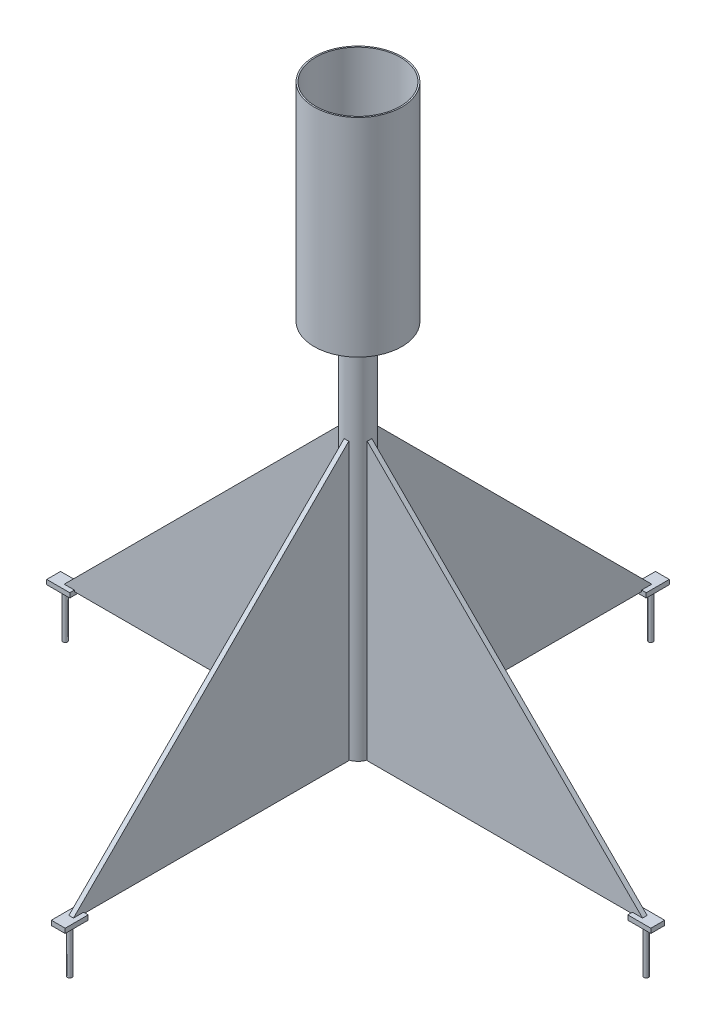
SolidWorks part; units mm, degrees
material "AISI 316 Stainless Steel Sheet (SS)"
ref_plane "Front Plane" through (0, 0, 0) normal (0, 0, 1) x (1, 0, 0)
ref_plane "Top Plane" through (0, 0, 0) normal (0, 1, 0) x (1, 0, 0)
ref_plane "Right Plane" through (0, 0, 0) normal (1, 0, 0) x (0, 0, -1)
sketch "Sketch1" plane through (0, 0, 0) normal (0, 1, 0) x (1, 0, 0)
  circle A0 centre (0, 0) radius 95
  dimension "D1" = 190
extrude "Boss-Extrude1" add sketch "Sketch1" along normal blind 450
shell "Shell2" thickness 3
sketch "Sketch2" plane through (0, 0, 0) normal (0, -1, 0) x (1, 0, 0)
  circle A0 centre (0, 0) radius 30
  dimension "D1" = 60
extrude "Boss-Extrude2" add sketch "Sketch2" along normal blind 805
shell "Shell3" thickness 3
sketch "Sketch5" plane through (0, 0, 0) normal (1, 0, 0) x (0, 0, -1)
  line L0 (-30, -805) -> (-30, -205) construction
  line L1 (-30, 0) -> (-30, -805) construction
  line L2 (-30, -205) -> (-630, -805) construction
  line L3 (-630, -805) -> (-30, -805) construction
  line L4 (-30, -205) -> (-630, -805)
  line L5 (-630, -805) -> (-30, -805)
  line L6 (-30, -805) -> (-30, -205)
  dimension "D1" = 600
  dimension "D2" = 600
extrude "Boss-Extrude3" add sketch "Sketch5" along normal blind 10 separate body
sketch "Sketch6" plane through (0, 0, 0) normal (1, 0, 0) x (0, 0, -1)
  line L0 (30, -805) -> (30, -205) construction
  line L1 (30, -805) -> (30, 0) construction
  line L2 (30, -205) -> (630, -805) construction
  line L3 (630, -805) -> (30, -805) construction
  line L4 (30, -205) -> (30, -805)
  line L5 (30, -805) -> (630, -805)
  line L6 (630, -805) -> (30, -205)
  dimension "D1" = 600
  dimension "D2" = 600
extrude "Boss-Extrude4" add sketch "Sketch6" along normal blind 10 separate body
sketch "Sketch8" plane through (0, 0, 0) normal (0, 0, 1) x (1, 0, 0)
  line L0 (-30, -805) -> (-30, -205) construction
  line L1 (-30, 0) -> (-30, -805) construction
  line L2 (-30, -205) -> (-630, -805) construction
  line L3 (-630, -805) -> (-30, -805) construction
  line L4 (-30, -205) -> (-30, -805)
  line L5 (-30, -805) -> (-630, -805)
  line L6 (-630, -805) -> (-30, -205)
  dimension "D1" = 600
  dimension "D2" = 600
extrude "Boss-Extrude5" add sketch "Sketch8" along normal blind 10 separate body
sketch "Sketch9" plane through (0, 0, 0) normal (0, 0, 1) x (1, 0, 0)
  line L0 (30, -805) -> (30, -205) construction
  line L1 (30, -805) -> (30, 0) construction
  line L2 (30, -205) -> (630, -805) construction
  line L3 (630, -805) -> (30, -805) construction
  line L4 (30, -205) -> (30, -805)
  line L5 (30, -805) -> (630, -805)
  line L6 (630, -805) -> (30, -205)
  dimension "D1" = 600
  dimension "D2" = 600
extrude "Boss-Extrude6" add sketch "Sketch9" along normal blind 10 separate body
ref_plane "Plane4" through (0, -802, 0) normal (0, -1, 0) x (-1, 0, 0)
sketch "Sketch11" plane through (0, -802, 0) normal (0, -1, 0) x (-1, 0, 0)
  line L0 (-10, 630) -> (-5, 630) construction
  line L1 (-10, 630) -> (0, 630) construction
  line L3 (-20, 605) -> (10, 605)
  line L4 (-20, 605) -> (-20, 655)
  line L5 (-20, 655) -> (10, 655)
  line L6 (10, 605) -> (10, 655)
  line L7 (-20, 605) -> (10, 655) construction
  line L8 (-20, 655) -> (10, 605) construction
  dimension "D1" = 50
  dimension "D2" = 30
extrude "Boss-Extrude7" add sketch "Sketch11" along normal blind 10
sketch "Sketch12" plane through (0, -802, 0) normal (0, -1, 0) x (-1, 0, 0)
  line L0 (630, 0) -> (630, -5) construction
  line L1 (630, -10) -> (630, 0) construction
  line L3 (605, -20) -> (655, -20)
  line L4 (605, -20) -> (605, 10)
  line L5 (605, 10) -> (655, 10)
  line L6 (655, -20) -> (655, 10)
  line L7 (605, -20) -> (655, 10) construction
  line L8 (605, 10) -> (655, -20) construction
  dimension "D1" = 50
  dimension "D2" = 30
extrude "Boss-Extrude8" add sketch "Sketch12" along normal blind 10
sketch "Sketch13" plane through (0, -802, 0) normal (0, -1, 0) x (-1, 0, 0)
  line L0 (-630, 0) -> (-630, -5) construction
  line L1 (-630, -10) -> (-630, 0) construction
  line L3 (-605, -20) -> (-655, -20)
  line L4 (-605, -20) -> (-605, 10)
  line L5 (-605, 10) -> (-655, 10)
  line L6 (-655, -20) -> (-655, 10)
  line L7 (-605, -20) -> (-655, 10) construction
  line L8 (-605, 10) -> (-655, -20) construction
  dimension "D1" = 50
  dimension "D2" = 30
extrude "Boss-Extrude9" add sketch "Sketch13" along normal blind 10
sketch "Sketch14" plane through (0, -802, 0) normal (0, -1, 0) x (-1, 0, 0)
  line L0 (-10, -630) -> (-5, -630) construction
  line L1 (-10, -630) -> (0, -630) construction
  line L3 (-20, -605) -> (10, -605)
  line L4 (-20, -605) -> (-20, -655)
  line L5 (-20, -655) -> (10, -655)
  line L6 (10, -605) -> (10, -655)
  line L7 (-20, -605) -> (10, -655) construction
  line L8 (-20, -655) -> (10, -605) construction
  dimension "D1" = 50
  dimension "D2" = 30
extrude "Boss-Extrude10" add sketch "Sketch14" along normal blind 10
sketch "Sketch17" plane through (0, -812, 0) normal (0, -1, 0) x (1, 0, 0)
  line L0 (605, 5) -> (630, 5) construction
  line L1 (605, 20) -> (605, -10) construction
  circle A0 centre (630, 5) radius 5
  dimension "D2" = 10
  dimension "D1" = 25
extrude "Boss-Extrude11" add sketch "Sketch17" along normal blind 100
sketch "Sketch18" plane through (0, -812, 0) normal (0, -1, 0) x (1, 0, 0)
  line L0 (5, 605) -> (5, 630) construction
  line L1 (0, 605) -> (10, 605) construction
  circle A0 centre (5, 630) radius 5
  dimension "D2" = 10
  dimension "D1" = 25
extrude "Boss-Extrude12" add sketch "Sketch18" along normal blind 100
sketch "Sketch19" plane through (0, -812, 0) normal (0, -1, 0) x (1, 0, 0)
  line L0 (-605, 5) -> (-630, 5) construction
  line L1 (-605, -10) -> (-605, 20) construction
  circle A0 centre (-630, 5) radius 5
  dimension "D2" = 10
  dimension "D1" = 25
extrude "Boss-Extrude13" add sketch "Sketch19" along normal blind 100
sketch "Sketch20" plane through (0, -812, 0) normal (0, -1, 0) x (1, 0, 0)
  line L0 (5, -605) -> (5, -630) construction
  line L1 (20, -605) -> (-10, -605) construction
  circle A0 centre (5, -630) radius 5
  dimension "D2" = 10
  dimension "D1" = 25
extrude "Boss-Extrude14" add sketch "Sketch20" along normal blind 100
